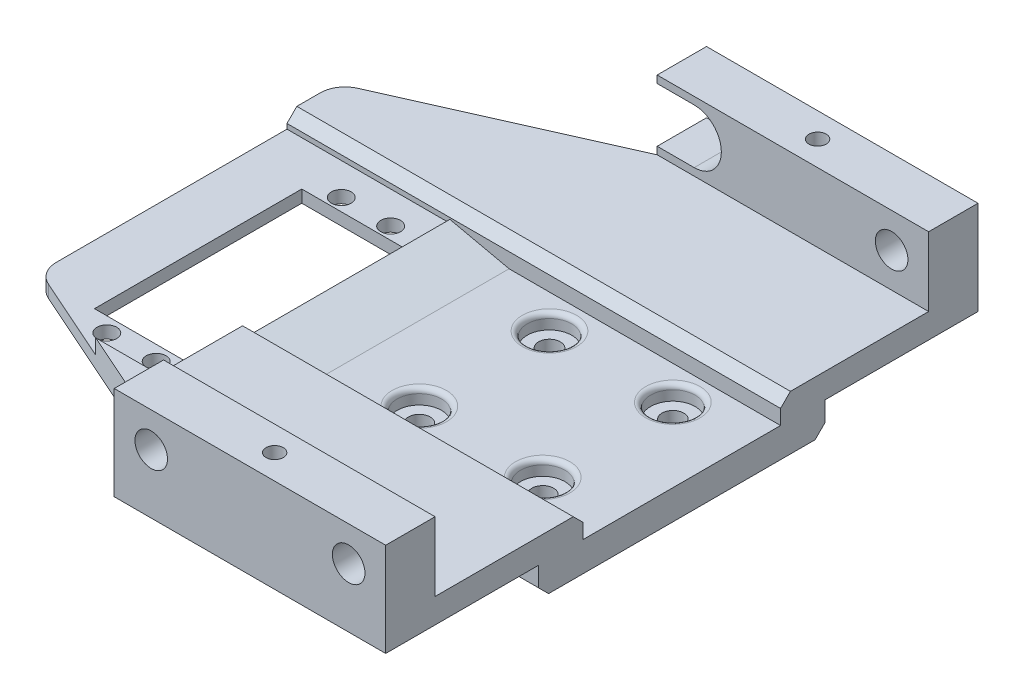
SolidWorks part; units mm, degrees
ref_plane "Alzado" through (0, 0, 0) normal (0, 0, 1) x (1, 0, 0)
ref_plane "Planta" through (0, 0, 0) normal (0, 1, 0) x (1, 0, 0)
ref_plane "Vista lateral" through (0, 0, 0) normal (1, 0, 0) x (0, 0, -1)
sketch "Croquis1" plane through (0, 0, 0) normal (0, 1, 0) x (1, 0, 0)
  line L1 (-27.5, -29) -> (27.5, -29)
  line L2 (-27.5, -29) -> (-27.5, 29)
  line L3 (-27.5, 29) -> (27.5, 29)
  line L4 (27.5, -29) -> (27.5, 29)
  line L5 (-27.5, -29) -> (27.5, 29) construction
  line L6 (-27.5, 29) -> (27.5, -29) construction
  circle A0 centre (-12.5, 13.1818) radius 2.2
  circle A1 centre (12.5, 13.1818) radius 2.2
  circle A2 centre (-12.5, -13.1818) radius 2.2
  circle A3 centre (12.5, -13.1818) radius 2.2
  point P0 (0, 0)
  dimension "D1" = 4.4
  dimension "D2" = 25
  dimension "D3" = 15
  dimension "D4" = 58
extrude "Saliente-Extruir1" add sketch "Croquis1" along normal blind 6
sketch "Croquis2" plane through (0, 6, 0) normal (0, 1, 0) x (1, 0, 0)
  circle A0 centre (-12.5, 13.1818) radius 4.5
  circle A1 centre (12.5, 13.1818) radius 4.5
  circle A2 centre (-12.5, -13.1818) radius 4.5
  circle A3 centre (12.5, -13.1818) radius 4.5
  dimension "D1" = 9
extrude "Cortar-Extruir1" cut sketch "Croquis2" against normal blind 3
fillet "Redondeo1" radius 1 4 edges at (-12.5, 6, 17.6818) (12.5, 6, 17.6818) (12.5, 6, -8.6818) (-12.5, 6, -8.6818)
sketch "Croquis3" plane through (0, 6, 0) normal (0, 1, 0) x (1, 0, 0)
  line L0 (-27.5, 20) -> (27.5, 20)
  line L1 (-27.5, 20) -> (-27.5, 60)
  line L2 (27.5, 20) -> (27.5, 60)
  line L3 (-27.5, 60) -> (27.5, 60)
  line L4 (-27.5, 29) -> (-27.5, -29) construction
  line L5 (27.5, -29) -> (27.5, 29) construction
  line L6 (-3.3, 0) -> (3.3, 0) construction
  line L7 (-27.5, -60) -> (27.5, -60)
  line L8 (27.5, -20) -> (27.5, -60)
  line L9 (-27.5, -20) -> (-27.5, -60)
  line L10 (-27.5, -20) -> (27.5, -20)
  dimension "D1" = 20
  dimension "D2" = 60
extrude "Saliente-Extruir2" add sketch "Croquis3" along normal blind 5
sketch "Croquis4" plane through (0, 11, 0) normal (0, 1, 0) x (1, 0, 0)
  line L0 (-27.5, 60) -> (27.5, 60)
  line L1 (-27.5, 60) -> (-27.5, 50)
  line L2 (27.5, 60) -> (27.5, 50)
  line L3 (-27.5, 50) -> (27.5, 50)
  line L4 (-6.05, 0) -> (6.05, 0) construction
  line L5 (-27.5, -50) -> (27.5, -50)
  line L6 (27.5, -60) -> (27.5, -50)
  line L7 (-27.5, -60) -> (-27.5, -50)
  line L8 (-27.5, -60) -> (27.5, -60)
  dimension "D1" = 10
extrude "Saliente-Extruir3" add sketch "Croquis4" along normal blind 14
sketch "Croquis5" plane through (0, 0, 0) normal (0, 0, 1) x (1, 0, 0)
  line L0 (0, -13.75) -> (0, 13.75) construction
  line L1 (-27.5, 25) -> (27.5, 25) construction
  circle A0 centre (-20, 18) radius 3.3
  circle A1 centre (20, 18) radius 3.3
  dimension "D1" = 6.6
  dimension "D2" = 40
  dimension "D3" = 7
extrude "Cortar-Extruir2" cut sketch "Croquis5" against normal through all both and the other way through all
sketch "Croquis6" plane through (0, 0, -60) normal (0, 0, -1) x (-1, 0, 0)
  line L0 (27.5, 23.5) -> (20, 23.5)
  line L1 (27.5, 25) -> (27.5, 6) construction
  line L2 (20, 12.5) -> (27.5, 12.5)
  line L3 (27.5, 12.5) -> (27.5, 23.5)
  arc A0 (20, 23.5) -> (20, 12.5) centre (20, 18) ccw
  circle A1 centre (20, 18) radius 3.3 construction
  dimension "D1" = 5.5
extrude "Cortar-Extruir3" cut sketch "Croquis6" against normal up to next
sketch "Croquis7" plane through (0, 11, 0) normal (0, 1, 0) x (1, 0, 0)
  line L0 (-72.5, 30) -> (-72.5, -30)
  line L1 (-13.75, 0) -> (13.75, 0) construction
  line L2 (-72.5, -30) -> (-27.5, -50)
  line L3 (-72.5, 30) -> (-27.5, 50)
  line L4 (-27.5, 50) -> (-27.5, 20) construction
  line L5 (-27.5, 50) -> (-27.5, -50)
  point P2 (-72.5, 0)
  dimension "D1" = 45
  dimension "D2" = 60
extrude "Saliente-Extruir4" add sketch "Croquis7" against normal up to surface (11 mm away) up to face at (-12.5, 0, 15.3818)
sketch "Croquis8" plane through (0, 0, -29) normal (0, 0, -1) x (-1, 0, 0)
  line L0 (27.5, 6) -> (47.5, 0)
  line L1 (30.25, 0) -> (-30.25, 0) construction
  line L2 (47.5, 0) -> (27.5, 0)
  line L3 (27.5, 0) -> (27.5, 6) construction
  line L4 (27.5, 0) -> (27.5, 6)
  dimension "D1" = 20
extrude "Cortar-Extruir4" cut sketch "Croquis8" along normal through all
mirror "Simetría1" about plane through (0, 0, 0) normal (0, 0, 1) of "Cortar-Extruir4"
sketch "Croquis9" plane through (0, 0, 0) normal (0, 0, 1) x (1, 0, 0)
  line L0 (-27.5, 6) -> (-50, 11)
  line L1 (-72.5, 11) -> (-27.5, 11) construction
  line L2 (-50, 11) -> (-27.5, 11)
  line L3 (-27.5, 25) -> (-27.5, 6) construction
  line L4 (-27.5, 11) -> (-27.5, 6)
  point P5 (0, 0)
  point P9 (0, 0)
  point P10 (-47.5, 11)
extrude "Cortar-Extruir5" cut sketch "Croquis9" against normal up to surface and the other way up to surface up to face at (0, 8.5, -20) other way up to face at (0, 8.5, 20)
sketch "Croquis10" plane through (0, 0, 0) normal (0, -1, 0) x (1, 0, 0)
  line L0 (-27.5, 29) -> (-27.5, 50) construction
  line L1 (-39.5, 31) -> (-60.5, 31)
  line L2 (-39.5, 31) -> (-39.5, -11)
  line L3 (-39.5, -11) -> (-60.5, -11)
  line L4 (-60.5, 31) -> (-60.5, -11)
  line L5 (-39.5, 31) -> (-60.5, -11) construction
  line L6 (-39.5, -11) -> (-60.5, 31) construction
  line L7 (-47.5, 29) -> (27.5, 29) construction
  point P0 (-50, 10)
  dimension "D1" = 33
  dimension "D2" = 2
  dimension "D3" = 42
  dimension "D4" = 12
extrude "Cortar-Extruir6" cut sketch "Croquis10" against normal through all
sketch "Croquis11" plane through (0, 0, 0) normal (0, -1, 0) x (1, 0, 0)
  line L8 (-39.5, -19) -> (-39.5, 44.6667)
  line L9 (-39.5, -19) -> (-72.5, -19)
  line L10 (-39.5, 44.6667) -> (-72.5, 44.6667)
  line L11 (-72.5, -19) -> (-72.5, 44.6667)
  line L12 (-27.5, 50) -> (-47.5, 41.1111) construction
  line L13 (-72.5, -30) -> (-72.5, 30) construction
  line L14 (-39.5, -11) -> (-39.5, 29) construction
  line L15 (-60.5, -11) -> (-39.5, -11) construction
  dimension "D1" = 8
extrude "Cortar-Extruir7" cut sketch "Croquis11" against normal blind 5.5
sketch "Croquis12" plane through (0, 5.5, 0) normal (0, -1, 0) x (1, 0, 0)
  line L0 (-39.5, 29) -> (27.5, 29) construction
  line L1 (-39.5, 44.6667) -> (-39.5, 29) construction
  line L2 (27.5, 10.25) -> (-72.5, 10.25) construction
  line L3 (27.5, 29) -> (27.5, -29) construction
  line L4 (-72.5, 30) -> (-72.5, -19) construction
  circle A0 centre (-45, 34) radius 2
  circle A1 centre (-55, 34) radius 2
  circle A2 centre (-55, -13.5) radius 2
  circle A3 centre (-45, -13.5) radius 2
  dimension "D1" = 10
  dimension "D2" = 4
  dimension "D3" = 5
  dimension "D4" = 5.5
  dimension "D5" = 18.75
extrude "Cortar-Extruir8" cut sketch "Croquis12" against normal through all
sketch "Croquis13" plane through (0, 11, 0) normal (0, 1, 0) x (1, 0, 0)
  line L0 (-72.5, 20) -> (-39.5, 20)
  line L1 (-72.5, 30) -> (-72.5, -30) construction
  line L2 (-39.5, 20) -> (-39.5, -39)
  line L3 (-39.5, -39) -> (-52.25, -39)
  line L4 (-72.5, -30) -> (-27.5, -50) construction
  line L5 (-50, 20) -> (-27.5, 20) construction
  line L6 (-39.5, -20) -> (-39.5, -31) construction
  line L7 (-72.5, -30) -> (-52.25, -39)
  line L8 (-72.5, 20) -> (-72.5, -30)
  point P7 (-45, -34)
  dimension "D1" = 5
extrude "Cortar-Extruir9" cut sketch "Croquis13" against normal blind 3
chamfer "Chaflán1" distance 2 angle 45 5 edges at (-6, 11, 20) (-22.5, 11, -20) (-10, 0, -29) (-6, 0, 29) (-56, 0, -19)
sketch "Croquis14" plane through (0, 25, 0) normal (0, 1, 0) x (1, 0, 0)
  line L0 (0, -13.75) -> (0, 13.75) construction
  line L1 (-13.75, 0) -> (13.75, 0) construction
  line L2 (0, 60) -> (0, 50) construction
  line L3 (27.5, 60) -> (-27.5, 60) construction
  line L4 (-27.5, 50) -> (27.5, 50) construction
  circle A0 centre (0, 55) radius 1.75
  circle A1 centre (0, -55) radius 1.75
  point P14 (0, 62.2092)
  point P15 (0, 0)
  point P16 (0, 55)
  dimension "D1" = 3.5
extrude "Cortar-Extruir10" cut sketch "Croquis14" against normal through all
sketch "Croquis15" plane through (0, 6, 0) normal (0, -1, 0) x (1, 0, 0)
  line L0 (13.75, 0) -> (-13.75, 0) construction
  line L1 (3.8105, 55) -> (1.9053, 58.3)
  line L2 (1.9053, 58.3) -> (-1.9053, 58.3)
  line L3 (-1.9053, 58.3) -> (-3.8105, 55)
  line L4 (-3.8105, 55) -> (-1.9053, 51.7)
  line L5 (-1.9053, 51.7) -> (1.9053, 51.7)
  line L6 (1.9053, 51.7) -> (3.8105, 55)
  line L7 (1.9053, -51.7) -> (3.8105, -55)
  line L8 (-1.9053, -51.7) -> (1.9053, -51.7)
  line L9 (-3.8105, -55) -> (-1.9053, -51.7)
  line L10 (-1.9053, -58.3) -> (-3.8105, -55)
  line L11 (1.9053, -58.3) -> (-1.9053, -58.3)
  line L12 (3.8105, -55) -> (1.9053, -58.3)
  circle A0 centre (0, 55) radius 3.3 construction
  circle A1 centre (0, -55) radius 3.3 construction
  dimension "D1" = 6.6
extrude "Cortar-Extruir11" cut sketch "Croquis15" against normal blind 2.5
fillet "Redondeo2" radius 5 2 edges at (-72.5, 5.5, -30) (-72.5, 6.75, 30)
